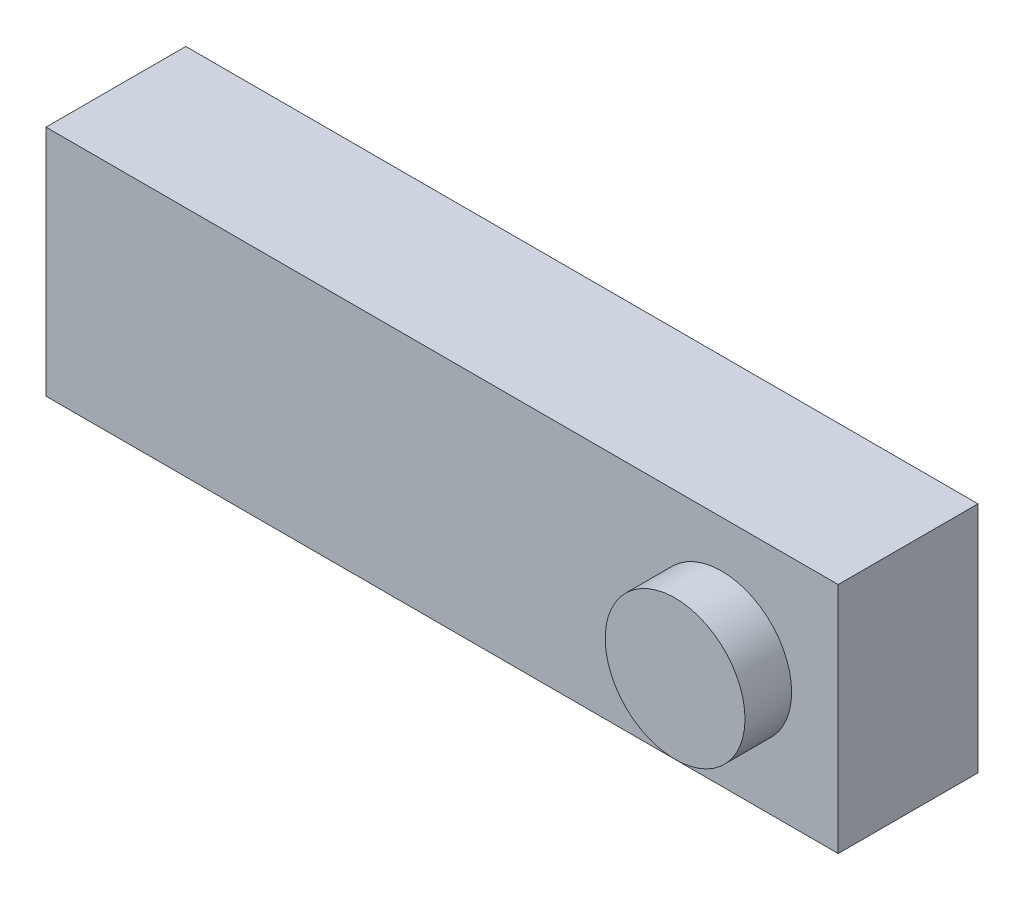
SolidWorks part; units mm, degrees
ref_plane "Alzado" through (0, 0, 0) normal (0, 0, 1) x (1, 0, 0)
ref_plane "Planta" through (0, 0, 0) normal (0, 1, 0) x (1, 0, 0)
ref_plane "Vista lateral" through (0, 0, 0) normal (1, 0, 0) x (0, 0, -1)
sketch "Croquis2" plane through (0, 0, 3.1716) normal (0, 0, 1) x (1, 0, 0)
  line L1 (491.8348, 1149.027) -> (1341.8348, 1149.027)
  line L2 (491.8348, 1149.027) -> (491.8348, 899.027)
  line L3 (491.8348, 899.027) -> (1341.8348, 899.027)
  line L4 (1341.8348, 1149.027) -> (1341.8348, 899.027)
  dimension "D1" = 850
  dimension "D2" = 250
extrude "Saliente-Extruir1" add sketch "Croquis2" along normal blind 150
sketch "Croquis3" plane through (0, 0, 3.1716) normal (0, 0, -1) x (-1, 0, 0)
  line L0 (-1341.8348, 1149.027) -> (-491.8348, 1149.027) construction
  line L1 (-491.8348, 1149.027) -> (-491.8348, 899.027) construction
  circle A0 centre (-616.8348, 1024.027) radius 75
  dimension "D1" = 150
  dimension "D2" = 125
  dimension "D3" = 125
extrude "Cortar-Extruir1" cut sketch "Croquis3" against normal blind 50
sketch "Croquis4" plane through (0, 0, 153.1716) normal (0, 0, 1) x (1, 0, 0)
  line L0 (1341.8348, 899.027) -> (1341.8348, 1149.027) construction
  line L2 (1341.8348, 1149.027) -> (491.8348, 1149.027) construction
  circle A0 centre (1216.8348, 1024.027) radius 75
  point P6 (1279.827, 899.027)
  dimension "D1" = 150
  dimension "D2" = 125
  dimension "D3" = 125
extrude "Saliente-Extruir2" add sketch "Croquis4" along normal blind 50
